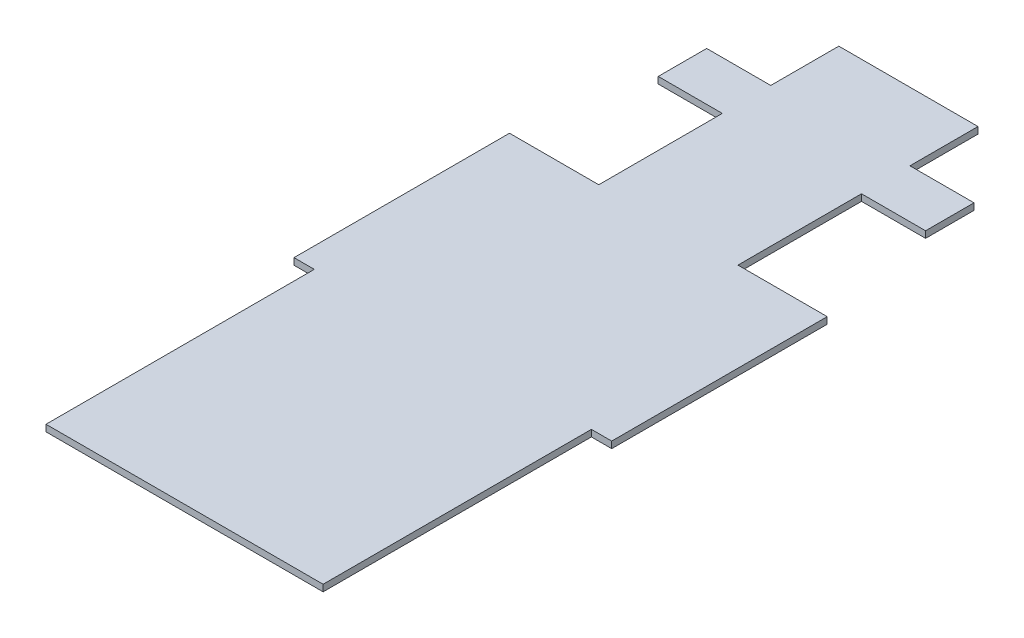
SolidWorks part; units mm, degrees
ref_plane "Plan de face" through (0, 0, 0) normal (0, 0, 1) x (1, 0, 0)
ref_plane "Plan de dessus" through (0, 0, 0) normal (0, 1, 0) x (1, 0, 0)
ref_plane "Plan de droite" through (0, 0, 0) normal (1, 0, 0) x (0, 0, -1)
sketch "Esquisse1" plane through (0, 0, 0) normal (0, 1, 0) x (1, 0, 0)
  line L3 (45, -30.525) -> (45, 30.525)
  line L5 (-45, -30.525) -> (-45, 30.525)
  line L10 (-19.715, 79.245) -> (-19.715, 98.525)
  line L12 (19.715, 98.525) -> (-19.715, 98.525)
  line L15 (-19.715, 65.525) -> (-37.865, 65.525)
  line L16 (-19.715, 79.245) -> (-37.865, 79.245)
  line L17 (-37.865, 79.245) -> (-37.865, 65.525)
  line L18 (19.715, 79.245) -> (37.865, 79.245)
  line L19 (37.865, 79.245) -> (37.865, 65.525)
  line L20 (37.865, 65.525) -> (19.715, 65.525)
  line L21 (-19.715, 65.525) -> (-19.715, 30.525)
  line L22 (19.715, 98.525) -> (19.715, 79.245)
  line L23 (-39.25, -106.525) -> (39.25, -106.525)
  line L24 (-39.25, -106.525) -> (-39.25, -30.525)
  line L25 (39.25, -106.525) -> (39.25, -30.525)
  line L26 (19.715, 65.525) -> (19.715, 30.525)
  line L27 (-45, 30.525) -> (-19.715, 30.525)
  line L28 (19.715, 30.525) -> (45, 30.525)
  line L29 (-45, -30.525) -> (-39.25, -30.525)
  line L30 (39.25, -30.525) -> (45, -30.525)
  dimension "D1" = 39.43
  dimension "D2" = 35
  dimension "D3" = 13.72
  dimension "D4" = 18.15
extrude "Boss.-Extru.6" add sketch "Esquisse1" along normal blind 1.87 contours L5 L27 L21 L15 L17 L16 L10 L12 L22 L18 L19 L20 L26 L28 L3 L30 L25 L23 L24 L29
